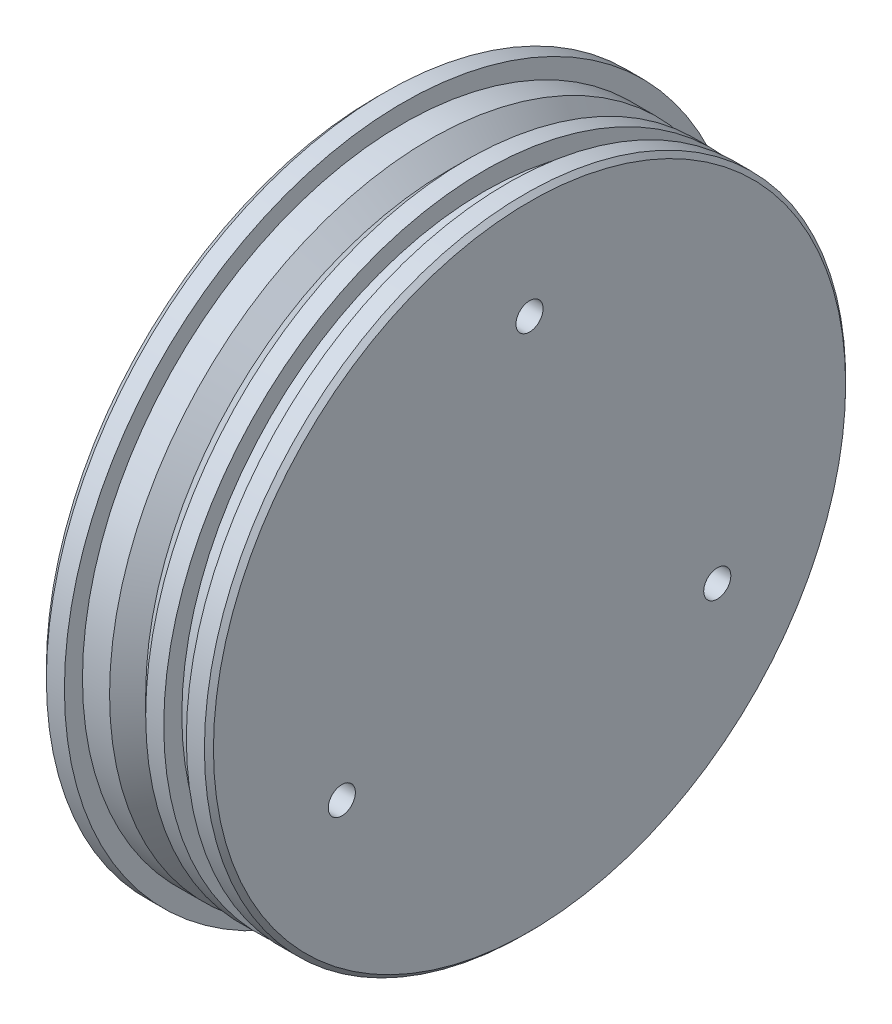
SolidWorks part; units mm, degrees
material "1060 Сплав"
ref_plane "Спереди" through (0, 0, 0) normal (0, 0, 1) x (1, 0, 0)
ref_plane "Сверху" through (0, 0, 0) normal (0, 1, 0) x (1, 0, 0)
ref_plane "Справа" through (0, 0, 0) normal (1, 0, 0) x (0, 0, -1)
sketch "Эскиз1" plane through (0, 0, 0) normal (0, 0, 1) x (1, 0, 0)
  line L0 (0, 0) -> (75.9362, 0) construction
  line L1 (-17, 0) -> (-17, 36.5)
  line L2 (-16, 37.5) -> (-14, 37.5)
  line L3 (-14, 37.5) -> (-14, 35.5)
  line L4 (-14, 35.5) -> (-11, 35.5)
  line L5 (-11, 35.5) -> (-9, 33.5)
  line L6 (-9, 33.5) -> (-7, 35.5)
  line L7 (-7, 35.5) -> (-5, 35.5)
  line L8 (-5, 35.5) -> (-5, 33.5)
  line L9 (-5, 33.5) -> (-2.5, 33.5)
  line L10 (-2.5, 33.5) -> (-2.5, 35.5)
  line L11 (-2.5, 35.5) -> (-0.5, 35.5)
  line L12 (0, 35) -> (0, 0)
  line L15 (-17, 36.5) -> (-16, 37.5)
  line L16 (-0.5, 35.5) -> (0, 35)
  line L18 (-17, 0) -> (0, 0)
  point P5 (-17, 37.5)
  point P16 (0, 35.5)
  dimension "D1" = 135
  dimension "D2" = 2
  dimension "D3" = 3
  dimension "D4" = 2.5
  dimension "D6" = 2
  dimension "D7" = 5
  dimension "D8" = 2
  dimension "D9" = 2.5
  dimension "D10" = 2
  dimension "D11" = 75
revolve "Повернуть1" add sketch "Эскиз1" angle 360 about L0
sketch "Эскиз2" plane through (0, 0, 0) normal (1, 0, 0) x (0, 0, -1)
  line L0 (0, 0) -> (0, 35) construction
  line L1 (0, 0) -> (30.3109, -17.5) construction
  line L2 (0, 0) -> (-30.3109, -17.5) construction
  circle A0 centre (20.7846, -12) radius 1.5
  circle A4 centre (0, 24) radius 1.5
  circle A5 centre (-20.7846, -12) radius 1.5
  point P1 (0, 0)
  point P4 (0, -8.7628)
  point P12 (0, -4.2025)
  point P16 (0, 0)
  dimension "D2" = 3
  dimension "D3" = 24
  dimension "D4" = 0
  dimension "D1" = 3
extrude "Вырез-Вытянуть1" cut sketch "Эскиз2" against normal blind 10
sketch "Эскиз3" plane through (0, 0, 0) normal (1, 0, 0) x (0, 0, -1)
  line L0 (0, 35) -> (0, -35.5) construction
  circle A0 centre (0, 0) radius 35 construction
  circle A1 centre (0, 0) radius 35.5 construction
